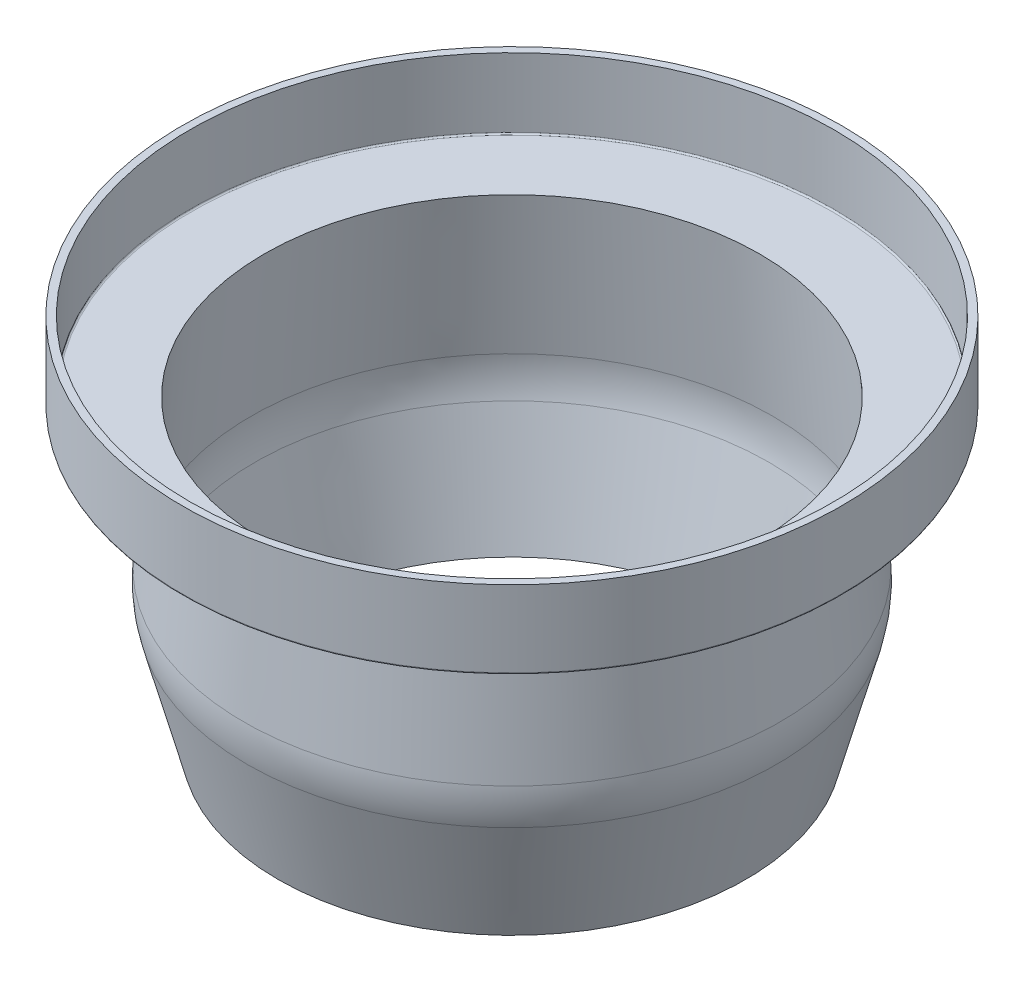
SolidWorks part; units mm, degrees
ref_plane "Ön Düzlem" through (0, 0, 0) normal (0, 0, 1) x (1, 0, 0)
ref_plane "Üst Düzlem" through (0, 0, 0) normal (0, 1, 0) x (1, 0, 0)
ref_plane "Sağ Düzlem" through (0, 0, 0) normal (1, 0, 0) x (0, 0, -1)
sketch "Çizim1" plane through (0, 0, 0) normal (0, 0, 1) x (1, 0, 0)
  line L0 (0, 0) -> (0, 31.7593) construction
  line L1 (-44, 30.8889) -> (-44, 21.0889)
  line L2 (-43.8, 20.8889) -> (-34, 20.8889)
  line L3 (-34, 20.8889) -> (-35.6942, 1.5237)
  line L4 (-35.2402, -3.6659) -> (-31.1017, -19.1111)
  line L5 (-44.5, 30.8889) -> (-44.5, 20.5889)
  line L6 (-44.3, 20.3889) -> (-34.5457, 20.3889)
  line L7 (-34.5457, 20.3889) -> (-36.2, 1.4795)
  line L8 (-35.746, -3.7101) -> (-31.5846, -19.2405)
  line L9 (-43.5, 30.8889) -> (-43.5, 21.5889)
  line L10 (-43.3, 21.3889) -> (-33.4543, 21.3889)
  line L11 (-33.4543, 21.3889) -> (-35.1885, 1.568)
  line L12 (-34.7344, -3.6216) -> (-30.6187, -18.9817)
  line L13 (-44.5, 30.8889) -> (-43.5, 30.8889)
  line L14 (-31.5846, -19.2405) -> (-30.6187, -18.9817)
  line L15 (-44, 30.8889) -> (-44, 20.8889) construction
  line L16 (-44, 20.8889) -> (-34, 20.8889) construction
  line L17 (-43.5, 30.8889) -> (-43.5, 21.3889) construction
  line L18 (-43.5, 21.3889) -> (-33.4543, 21.3889) construction
  line L19 (-44.5, 30.8889) -> (-44.5, 20.3889) construction
  line L20 (-44.5, 20.3889) -> (-34.5457, 20.3889) construction
  line L21 (-34.5457, 20.3889) -> (-36.4305, -1.1554) construction
  line L22 (-36.4305, -1.1554) -> (-31.5846, -19.2405) construction
  line L23 (-34, 20.8889) -> (-35.9248, -1.1111) construction
  line L24 (-35.9248, -1.1111) -> (-31.1017, -19.1111) construction
  line L25 (-33.4543, 21.3889) -> (-35.419, -1.0669) construction
  line L26 (-35.419, -1.0669) -> (-30.6187, -18.9817) construction
  arc A0 (-44, 21.0889) -> (-43.8, 20.8889) centre (-43.8, 21.0889) ccw
  arc A1 (-43.5, 21.5889) -> (-43.3, 21.3889) centre (-43.3, 21.5889) ccw
  arc A2 (-44.5, 20.5889) -> (-44.3, 20.3889) centre (-44.3, 20.5889) ccw
  arc A3 (-36.2, 1.4795) -> (-35.746, -3.7101) centre (-21.2571, 0.1721) ccw
  arc A4 (-35.6942, 1.5237) -> (-35.2402, -3.6659) centre (-20.7513, 0.2164) ccw
  arc A5 (-35.1885, 1.568) -> (-34.7344, -3.6216) centre (-20.2455, 0.2606) ccw
  point P36 (0, 0)
  point P37 (0, 0)
  dimension "D1" = 0.2
  dimension "D2" = 15
  dimension "D3" = 85
  dimension "D4" = 160
  dimension "D9" = 44
  dimension "D7" = 0.5
  dimension "D8" = 0.5
revolve "Döndür1" add sketch "Çizim1" angle 360 about L0
